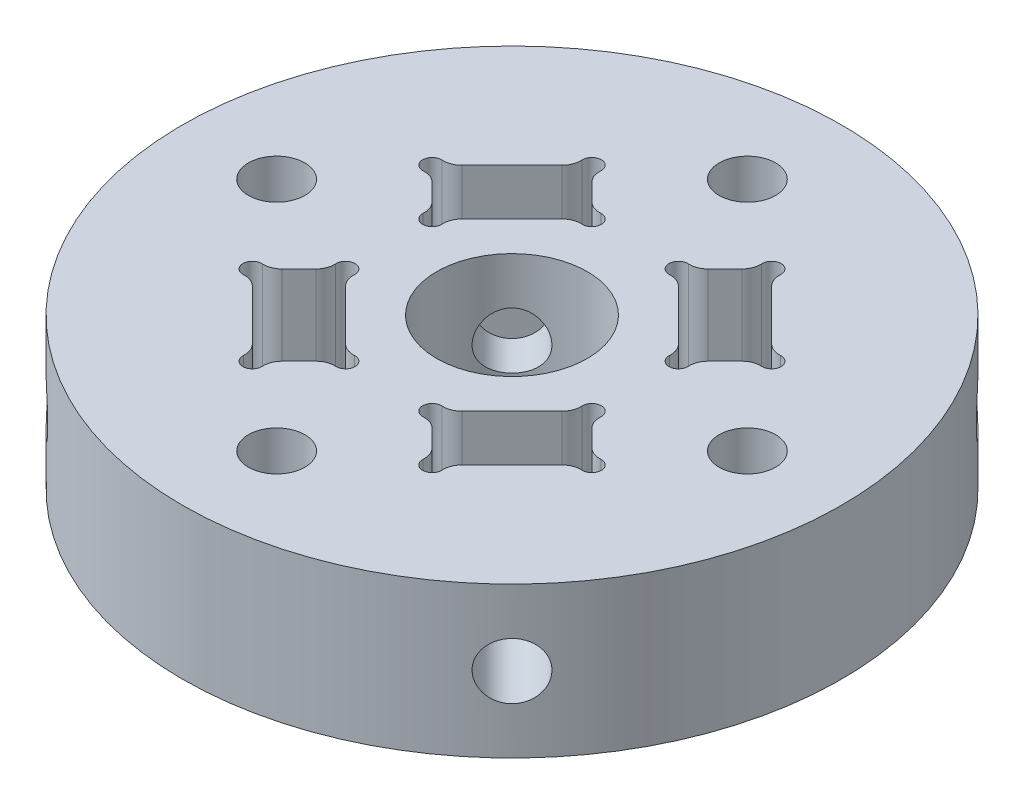
SolidWorks part; units mm, degrees
material "ABS PC"
ref_plane "Front Plane" through (0, 0, 0) normal (0, 0, 1) x (1, 0, 0)
ref_plane "Top Plane" through (0, 0, 0) normal (0, 1, 0) x (1, 0, 0)
ref_plane "Right Plane" through (0, 0, 0) normal (1, 0, 0) x (0, 0, -1)
sketch "Sketch1" plane through (0, 0, 0) normal (0, 1, 0) x (1, 0, 0)
  line L0 (0, 0) -> (-12.3744, 12.3744)
  line L1 (0, 0) -> (0, 8.8553)
  line L2 (0, 0) -> (-5.6569, 5.6569)
  line L3 (-5.6569, 5.6569) -> (-4.4194, 4.4194)
  line L4 (-4.4194, 4.4194) -> (-2.2981, 6.5407)
  line L5 (-2.2981, 6.5407) -> (-4.773, 9.0156)
  line L6 (-4.773, 9.0156) -> (-9.0156, 4.773)
  line L7 (-9.0156, 4.773) -> (-6.5407, 2.2981)
  line L8 (-6.5407, 2.2981) -> (-4.4194, 4.4194)
  line L9 (4.4194, 4.4194) -> (6.5407, 2.2981)
  line L10 (6.5407, 2.2981) -> (9.0156, 4.773)
  line L11 (9.0156, 4.773) -> (4.773, 9.0156)
  line L12 (4.773, 9.0156) -> (2.2981, 6.5407)
  line L13 (2.2981, 6.5407) -> (4.4194, 4.4194)
  line L14 (4.4194, -4.4194) -> (2.2981, -6.5407)
  line L15 (2.2981, -6.5407) -> (4.773, -9.0156)
  line L16 (4.773, -9.0156) -> (9.0156, -4.773)
  line L17 (9.0156, -4.773) -> (6.5407, -2.2981)
  line L18 (6.5407, -2.2981) -> (4.4194, -4.4194)
  line L19 (-4.4194, -4.4194) -> (-6.5407, -2.2981)
  line L20 (-6.5407, -2.2981) -> (-9.0156, -4.773)
  line L21 (-9.0156, -4.773) -> (-4.773, -9.0156)
  line L22 (-4.773, -9.0156) -> (-2.2981, -6.5407)
  line L23 (-2.2981, -6.5407) -> (-4.4194, -4.4194)
  circle A0 centre (0, 0) radius 17.5
  circle A1 centre (0, 0) radius 4
  circle A2 centre (0, 0) radius 12.5
  circle A3 centre (0, 12.5) radius 1.5
  circle A4 centre (12.5, 0) radius 1.5
  circle A5 centre (0, -12.5) radius 1.5
  circle A6 centre (-12.5, 0) radius 1.5
  circle A7 centre (-2.2981, 6.5407) radius 0.5
  circle A8 centre (-4.773, 9.0156) radius 0.5
  circle A9 centre (-9.0156, 4.773) radius 0.5
  circle A10 centre (-6.5407, 2.2981) radius 0.5
  circle A11 centre (2.2981, 6.5407) radius 0.5
  circle A12 centre (6.5407, 2.2981) radius 0.5
  circle A13 centre (9.0156, 4.773) radius 0.5
  circle A14 centre (4.773, 9.0156) radius 0.5
  circle A15 centre (6.5407, -2.2981) radius 0.5
  circle A16 centre (2.2981, -6.5407) radius 0.5
  circle A17 centre (4.773, -9.0156) radius 0.5
  circle A18 centre (9.0156, -4.773) radius 0.5
  circle A19 centre (-2.2981, -6.5407) radius 0.5
  circle A20 centre (-6.5407, -2.2981) radius 0.5
  circle A21 centre (-9.0156, -4.773) radius 0.5
  circle A22 centre (-4.773, -9.0156) radius 0.5
  dimension "D1" = 35
  dimension "D2" = 5
  dimension "D3" = 4
  dimension "D6" = 4
  dimension "D4" = 45
  dimension "D5" = 8
extrude "Boss-Extrude1" add sketch "Sketch1" along normal blind 8
fillet "Fillet1" radius 1 32 edges at (-2.6517, 4, -6.1872) (-6.1872, 4, -2.6517) (-6.8943, 4, -2.6517) (-8.6621, 4, -5.1265) (-8.6621, 4, -4.4194) (-4.4194, 4, -8.6621) (-5.1265, 4, -8.6621) (-2.6517, 4, -6.8943) (2.6517, 4, -6.1872) (2.6517, 4, -6.8943) (5.1265, 4, -8.6621) (4.4194, 4, -8.6621) (8.6621, 4, -5.1265) (8.6621, 4, -4.4194) (6.8943, 4, -2.6517) (6.1872, 4, -2.6517) (2.6517, 4, 6.1872) (2.6517, 4, 6.8943) (4.4194, 4, 8.6621) (5.1265, 4, 8.6621) (8.6621, 4, 5.1265) (8.6621, 4, 4.4194) (6.8943, 4, 2.6517) (6.1872, 4, 2.6517) (-4.4194, 4, 8.6621) (-5.1265, 4, 8.6621) (-2.6517, 4, 6.8943) (-2.6517, 4, 6.1872) (-6.1872, 4, 2.6517) (-8.6621, 4, 5.1265) (-8.6621, 4, 4.4194) (-6.8943, 4, 2.6517)
sketch "Sketch2" plane through (0, 8, 0) normal (0, 1, 0) x (1, 0, 0)
  line L0 (4.4194, -4.4194) -> (12.3744, -12.3744)
  line L1 (5.7502, -3.0887) -> (3.0887, -5.7502) construction
  circle A0 centre (0, 0) radius 17.5 construction
ref_plane "Plane1" through (12.3744, 8, 12.3744) normal (0.7071, 0, 0.7071) x (0.7071, 0, -0.7071)
sketch "Sketch3" plane through (12.3744, 8, 12.3744) normal (0.7071, 0, 0.7071) x (0.7071, 0, -0.7071)
  line L0 (0, 0) -> (0, -8)
  circle A0 centre (0, -4) radius 1.5
extrude "Cut-Extrude1" cut sketch "Sketch3" against normal blind 19 contours A0
pattern_circular "CirPattern1" count 4 over 360 about axis through (0, 8, 0) along (0, 1, 0) of "Cut-Extrude1"
